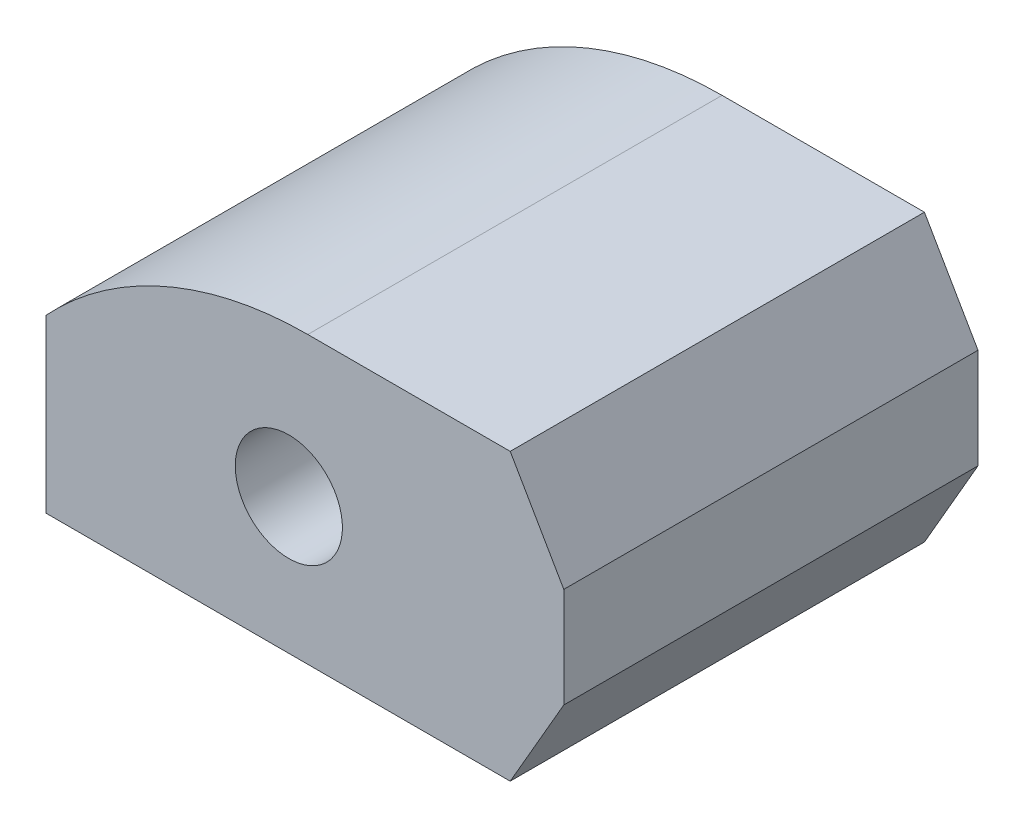
SolidWorks part; units mm, degrees
material "1060 Alloy"
ref_plane "Front Plane" through (0, 0, 0) normal (0, 0, 1) x (1, 0, 0)
ref_plane "Top Plane" through (0, 0, 0) normal (0, 1, 0) x (1, 0, 0)
ref_plane "Right Plane" through (0, 0, 0) normal (1, 0, 0) x (0, 0, -1)
sketch "Sketch1" plane through (0, 0, 0) normal (0, 0, 1) x (1, 0, 0)
  line L0 (15.3957, 0) -> (-15.3957, 0) construction
  line L1 (0, -13.679) -> (0, 13.679) construction
  line L2 (-34, 5) -> (-34, -19)
  line L3 (-34, -19) -> (31, -19)
  line L4 (31, -19) -> (38.5, -6.0096)
  line L5 (38.5, -6.0096) -> (38.5, 8.0096)
  line L6 (38.5, 8.0096) -> (31, 21)
  line L7 (31, 21) -> (2.6606, 21)
  circle A0 centre (0, 0) radius 7.5
  arc A1 (-34, 5) -> (2.6606, 21) centre (2.6606, -29) cw
  point P6 (0, 0)
  point P8 (0, 0)
  point P9 (0, 0)
  point P18 (0, 0)
  point P19 (0, 0)
  dimension "D1" = 15
  dimension "D10" = 50
  dimension "D2" = 19
  dimension "24" = 24
  dimension "D3" = 65
  dimension "D4" = 31
  dimension "D5" = 15
  dimension "D6" = 15
  dimension "D7" = 30
  dimension "D8" = 30
  dimension "D9" = 40
extrude "Boss-Extrude2" add sketch "Sketch1" along normal blind 58
equation "\"a\"= 58mm"
equation "\"b\"= 40mm"
equation "\"c\"= 65mm"
equation "\"D3@Sketch1\"=\"c\""
equation "\"D9@Sketch1\"=\"b\""
